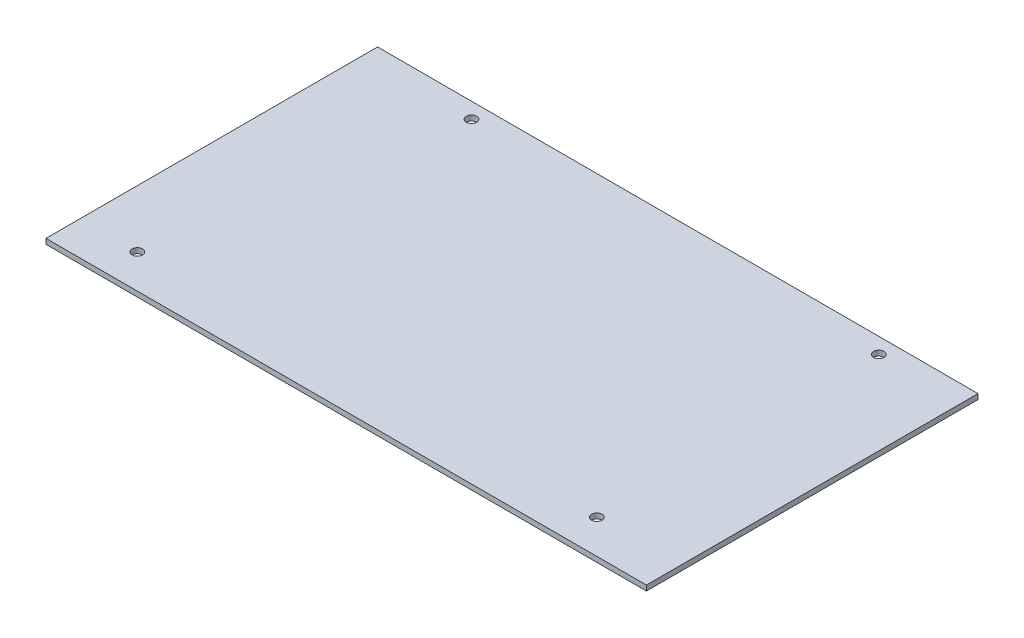
SolidWorks part; units mm, degrees
ref_plane "Front Plane" through (0, 0, 0) normal (0, 0, 1) x (1, 0, 0)
ref_plane "Top Plane" through (0, 0, 0) normal (0, 1, 0) x (1, 0, 0)
ref_plane "Right Plane" through (0, 0, 0) normal (1, 0, 0) x (0, 0, -1)
sketch "Sketch1" plane through (0, 0, 0) normal (0, 1, 0) x (1, 0, 0)
  line L1 (-57.5, 31.75) -> (57.5, 31.75)
  line L2 (-57.5, 31.75) -> (-57.5, -31.75)
  line L3 (-57.5, -31.75) -> (57.5, -31.75)
  line L4 (57.5, 31.75) -> (57.5, -31.75)
  line L5 (-57.5, 31.75) -> (57.5, -31.75) construction
  line L6 (-57.5, -31.75) -> (57.5, 31.75) construction
  circle A0 centre (-46.5, -25.25) radius 1
  circle A1 centre (-36.5, 28.75) radius 1
  circle A2 centre (41.5, 28.75) radius 1
  circle A3 centre (41.5, -25.25) radius 1
  point P0 (0, 0)
  point P14 (41.5, 28.203)
  dimension "D3" = 2
  dimension "D1" = 115
  dimension "D2" = 63.5
  dimension "D4" = 54
  dimension "D5" = 78
  dimension "D6" = 88
  dimension "D7" = 21
  dimension "D8" = 16
  dimension "D9" = 3
extrude "Boss-Extrude1" add sketch "Sketch1" along normal blind 1
